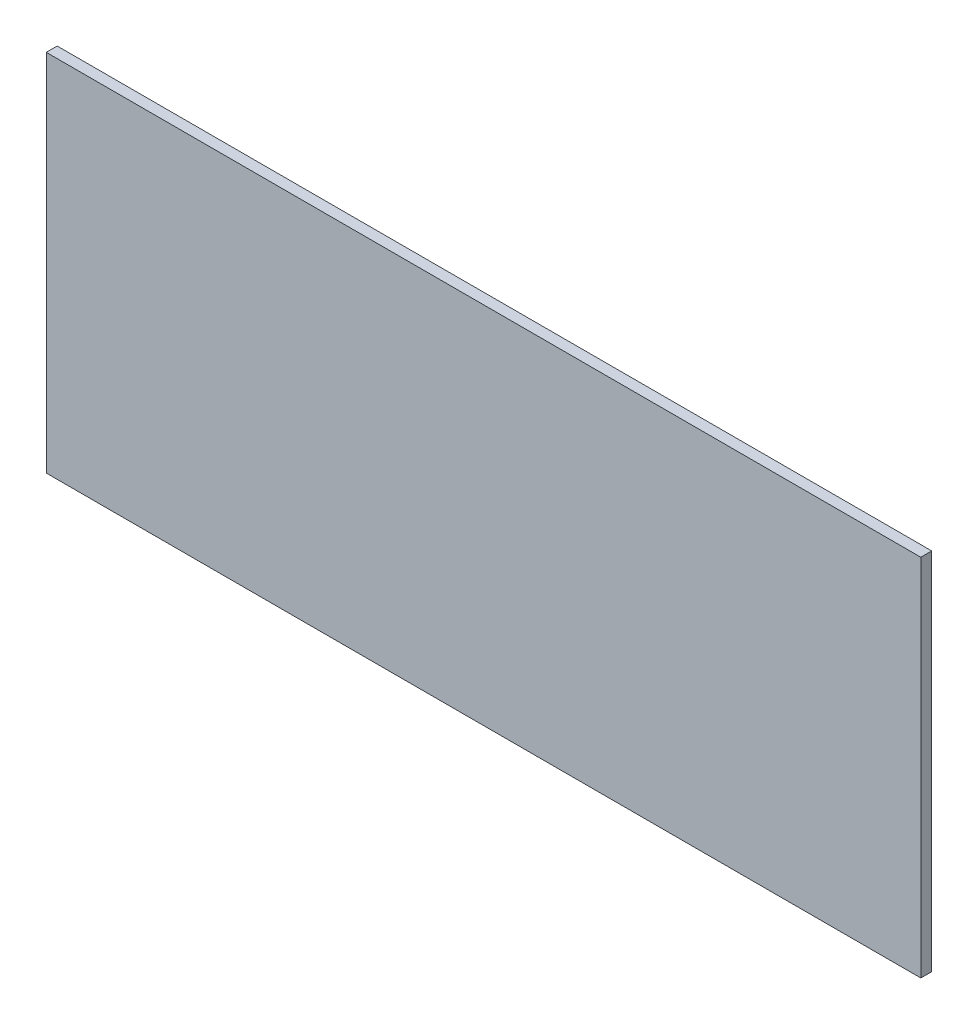
SolidWorks part; units mm, degrees
ref_plane "Front Plane" through (0, 0, 0) normal (0, 0, 1) x (1, 0, 0)
ref_plane "Top Plane" through (0, 0, 0) normal (0, 1, 0) x (1, 0, 0)
ref_plane "Right Plane" through (0, 0, 0) normal (1, 0, 0) x (0, 0, -1)
sketch "Sketch1" plane through (0, 0, 0) normal (0, 0, 1) x (1, 0, 0)
  line L1 (0, 0) -> (1200, 0)
  line L2 (0, 0) -> (0, 500)
  line L3 (0, 500) -> (1200, 500)
  line L4 (1200, 0) -> (1200, 500)
  dimension "D1" = 500
  dimension "D2" = 1200
extrude "Boss-Extrude1" add sketch "Sketch1" along normal blind 15
